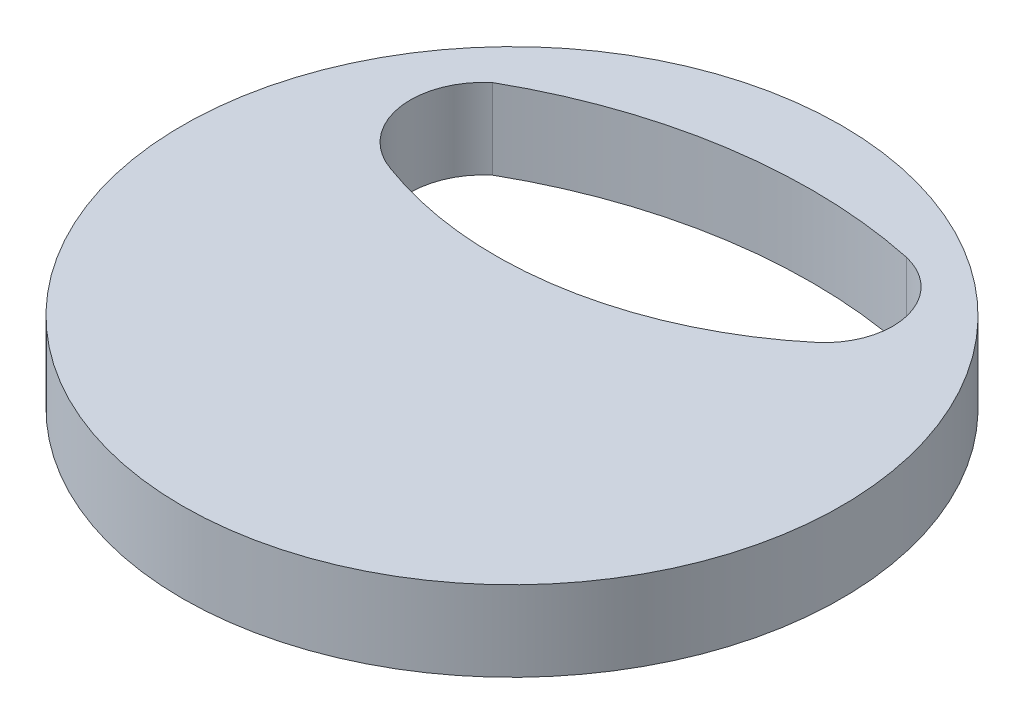
SolidWorks part; units mm, degrees
ref_plane "Front Plane" through (0, 0, 0) normal (0, 0, 1) x (1, 0, 0)
ref_plane "Top Plane" through (0, 0, 0) normal (0, 1, 0) x (1, 0, 0)
ref_plane "Right Plane" through (0, 0, 0) normal (1, 0, 0) x (0, 0, -1)
sketch "Sketch1" plane through (0, 0, 0) normal (0, 1, 0) x (1, 0, 0)
  circle A0 centre (0, 0) radius 7.4
  dimension "D1" = 14.8
extrude "Boss-Extrude1" add sketch "Sketch1" along normal blind 1.8
sketch "Sketch2" plane through (0, 1.8, 0) normal (0, 1, 0) x (1, 0, 0)
  arc A2 (-4.7552, 4.3139) -> (-4.2257, 1.4984) centre (-3.6911, 3.0564) ccw
  arc A4 (-4.7552, 4.3139) -> (3.2882, 5.5662) centre (0.9179, -5.6668) cw
  arc A6 (3.9477, 2.9077) -> (3.2882, 5.5662) centre (2.9453, 4.0701) ccw
  arc A7 (-4.2257, 1.4984) -> (3.9477, 2.9077) centre (-1.3524, 9.2402) ccw
extrude "Cut-Extrude1" cut sketch "Sketch2" against normal blind 1.8
